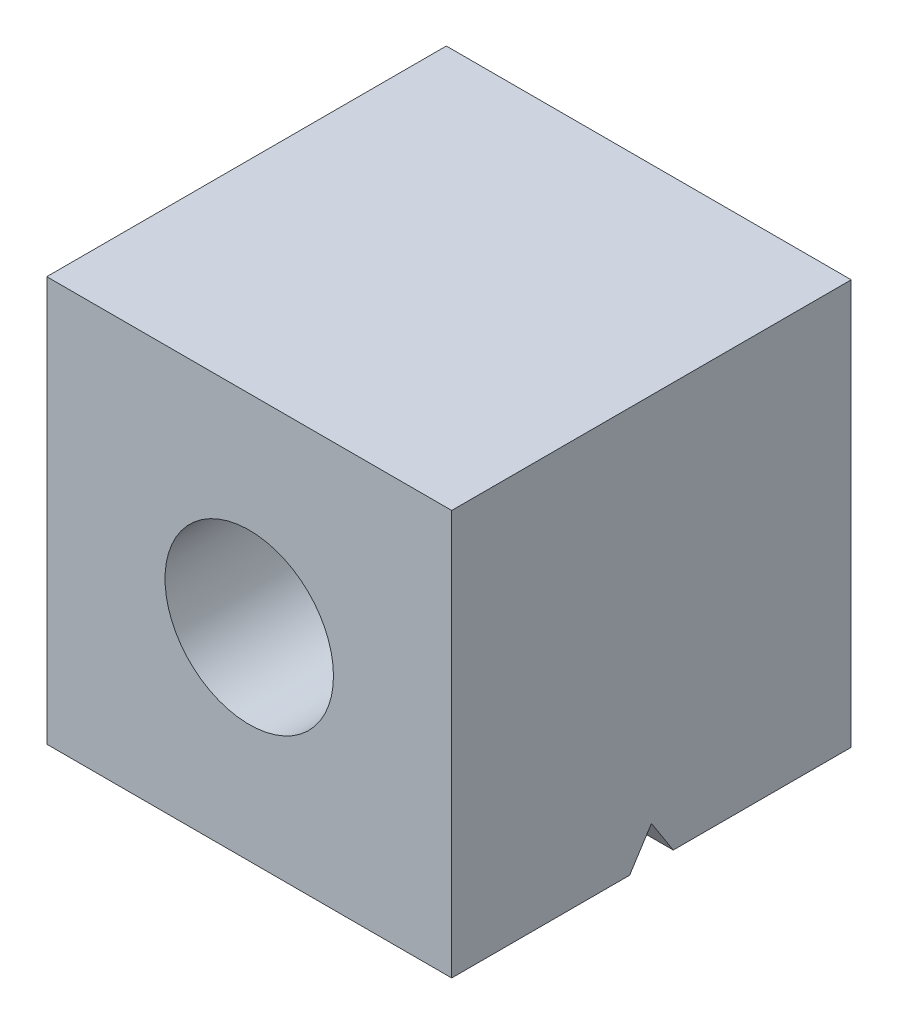
SolidWorks part; units mm, degrees
ref_plane "Front Plane" through (0, 0, 0) normal (0, 0, 1) x (1, 0, 0)
ref_plane "Top Plane" through (0, 0, 0) normal (0, 1, 0) x (1, 0, 0)
ref_plane "Right Plane" through (0, 0, 0) normal (1, 0, 0) x (0, 0, -1)
sketch "Sketch1" plane through (0, 0, 0) normal (0, 0, 1) x (1, 0, 0)
  line L1 (-9.525, 9.525) -> (9.525, 9.525)
  line L2 (-9.525, 9.525) -> (-9.525, -9.525)
  line L3 (-9.525, -9.525) -> (9.525, -9.525)
  line L4 (9.525, 9.525) -> (9.525, -9.525)
  line L5 (-9.525, 9.525) -> (9.525, -9.525) construction
  line L6 (-9.525, -9.525) -> (9.525, 9.525) construction
  point P0 (0, 0)
  dimension "D1" = 19.05
  dimension "D2" = 19.05
extrude "Boss-Extrude1" add sketch "Sketch1" along normal blind 18.796
sketch "Sketch2" plane through (0, 0, 18.796) normal (0, 0, 1) x (1, 0, 0)
  circle A0 centre (0, 0) radius 3.9624
  dimension "D1" = 7.9248
extrude "Cut-Extrude1" cut sketch "Sketch2" against normal through all
sketch "Sketch3" plane through (0, 0, 0) normal (1, 0, 0) x (0, 0, -1)
  line L0 (-10.4245, -9.525) -> (-9.398, -7.9248)
  line L1 (-18.796, -9.525) -> (0, -9.525) construction
  line L2 (-9.398, -7.9248) -> (-9.398, -9.6519) construction
  line L3 (-8.3715, -9.525) -> (-9.398, -7.9248)
  dimension "D1" = 1.6002
  dimension "D2" = 9.398
extrude "Cut-Extrude2" cut sketch "Sketch3" against normal through all and the other way through all
